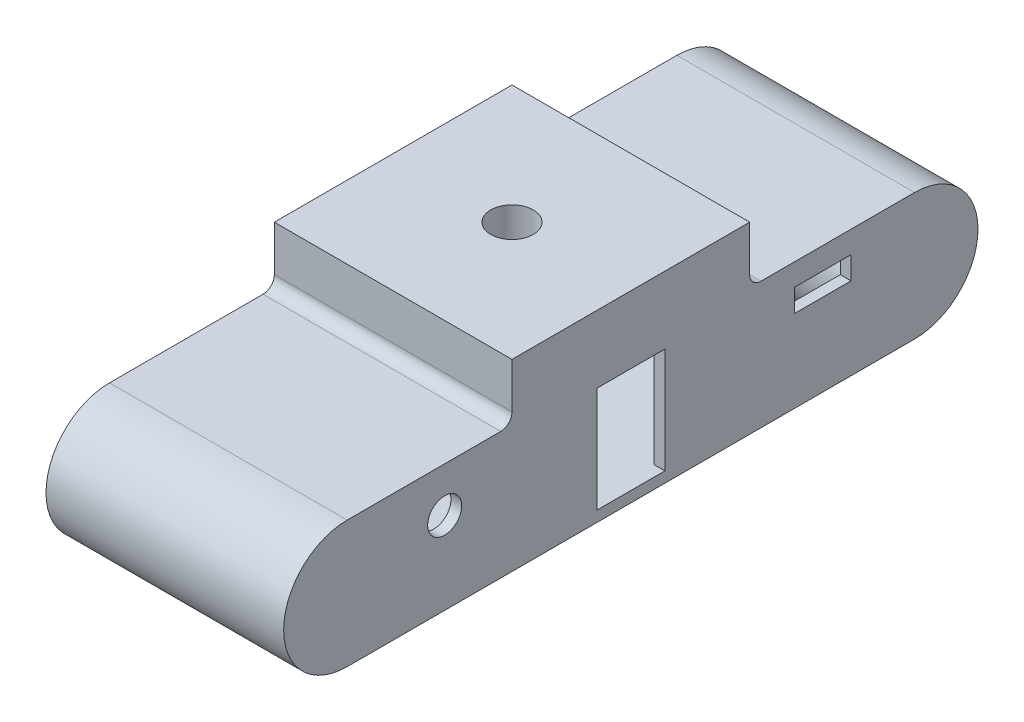
SolidWorks part; units mm, degrees
ref_plane "Front Plane" through (0, 0, 0) normal (0, 0, 1) x (1, 0, 0)
ref_plane "Top Plane" through (0, 0, 0) normal (0, 1, 0) x (1, 0, 0)
ref_plane "Right Plane" through (0, 0, 0) normal (1, 0, 0) x (0, 0, -1)
sketch "Sketch1" plane through (0, 0, 0) normal (1, 0, 0) x (0, 0, -1)
  line L0 (-63.5, 0) -> (63.5, 0) construction
  line L1 (-63.5, 14.211) -> (63.5, 14.211)
  line L4 (-63.5, -14.211) -> (63.5, -14.211)
  line L6 (-55.5973, 11.811) -> (55.5973, 11.811)
  line L8 (-55.5973, -11.811) -> (55.5973, -11.811)
  circle A0 centre (-63.5, 0) radius 11.811
  arc A2 (-63.5, 14.211) -> (-63.5, -14.211) centre (-63.5, 0) ccw
  arc A3 (63.5, -14.211) -> (63.5, 14.211) centre (63.5, 0) ccw
  circle A4 centre (63.5, 0) radius 11.811
  arc A5 (-55.5973, -11.811) -> (-55.5973, 11.811) centre (-63.5, 0) ccw
  arc A6 (55.5973, 11.811) -> (55.5973, -11.811) centre (63.5, 0) ccw
  point P7 (0, 0)
  dimension "D1" = 23.622
  dimension "D3" = 2.4
  dimension "D2" = 127
  dimension "D4" = 2.4
  dimension "D5" = 2.4
extrude "Boss-Extrude1" add sketch "Sketch1" along normal blind 50.8
sketch "Sketch2" plane through (50.8, 0, 0) normal (1, 0, 0) x (0, 0, -1)
  line L0 (-63.5, -14.211) -> (63.5, -14.211) construction
  line L1 (63.5, 14.211) -> (-63.5, 14.211) construction
  line L2 (-63.5, -14.211) -> (63.5, -14.211)
  line L3 (63.5, 14.211) -> (-63.5, 14.211)
  arc A0 (63.5, -14.211) -> (63.5, 14.211) centre (63.5, 0) ccw construction
  arc A1 (-63.5, 14.211) -> (-63.5, -14.211) centre (-63.5, 0) ccw construction
  arc A2 (63.5, -14.211) -> (63.5, 14.211) centre (63.5, 0) ccw
  arc A3 (-63.5, 14.211) -> (-63.5, -14.211) centre (-63.5, 0) ccw
extrude "Boss-Extrude2" add sketch "Sketch2" along normal blind 2.4
sketch "Sketch5" plane through (50.8, 0, 0) normal (-1, 0, 0) x (0, 0, 1)
  line L0 (-55.5973, 11.811) -> (55.5973, 11.811) construction
  line L1 (-49.289, 4.191) -> (-36.589, 4.191)
  line L2 (-49.289, 4.191) -> (-49.289, 9.271)
  line L3 (-49.289, 9.271) -> (-36.589, 9.271)
  line L4 (-36.589, 4.191) -> (-36.589, 9.271)
  line L6 (-55.5973, 11.811) -> (55.5973, 11.811) construction
  line L7 (-7.62, 11.811) -> (7.62, 11.811)
  line L8 (-7.62, 11.811) -> (-7.62, -11.811)
  line L9 (-7.62, -11.811) -> (7.62, -11.811)
  line L10 (7.62, 11.811) -> (7.62, -11.811)
  line L11 (55.5973, -11.811) -> (-55.5973, -11.811) construction
  arc A0 (-55.5973, -11.811) -> (-55.5973, 11.811) centre (-63.5, 0) ccw construction
  circle A1 centre (41.669, 4.191) radius 3.81
  arc A2 (55.5973, 11.811) -> (55.5973, -11.811) centre (63.5, 0) ccw construction
  point P20 (0, 11.811)
  point P22 (-7.62, 0)
  dimension "D3" = 7.62
  dimension "D1" = 5.08
  dimension "D2" = 12.7
  dimension "D4" = 7.62
  dimension "D5" = 7.62
  dimension "D6" = 2.54
  dimension "D7" = 15.24
extrude "Cut-Extrude3" cut sketch "Sketch5" against normal blind 3.81
sketch "Sketch8" plane through (0, 14.211, 0) normal (0, 1, 0) x (1, 0, 0)
  line L0 (53.2, 63.5) -> (53.2, -63.5) construction
  line L2 (0, 63.5) -> (0, -63.5) construction
  line L3 (53.2, -26.6) -> (0, -26.6)
  line L4 (53.2, -26.6) -> (53.2, 26.6)
  line L5 (53.2, 26.6) -> (0, 26.6)
  line L6 (0, -26.6) -> (0, 26.6)
  point P1 (53.2, 0)
  point P2 (0, 0)
extrude "Boss-Extrude3" add sketch "Sketch8" along normal blind 12.7
sketch "Sketch6" plane through (0, 14.211, 0) normal (0, 1, 0) x (1, 0, 0)
  line L0 (53.2, 26.6) -> (0, 26.6) construction
  circle A0 centre (26.6, 0) radius 4.7625
  point P4 (26.6, 26.6)
  dimension "D1" = 9.525
extrude "Cut-Extrude5" cut sketch "Sketch6" along normal through all and the other way blind 3.81
fillet "Fillet1" radius 2.54 2 edges at (26.6, 14.211, 26.6) (26.6, 14.211, -26.6)
equation "\"shell_thickness\"= \"wall_count\" * \"extrusion_width\" * 2"
equation "\"D4@Sketch1\"=\"shell_thickness\""
equation "\"D3@Sketch1\"=\"shell_thickness\""
equation "\"D1@Boss-Extrude2\"=\"shell_thickness\""
equation "\"D5@Sketch1\"=\"shell_thickness\""
equation "\"wall_count\"= 3"
equation "\"extrusion_width\"= 0.4mm"
